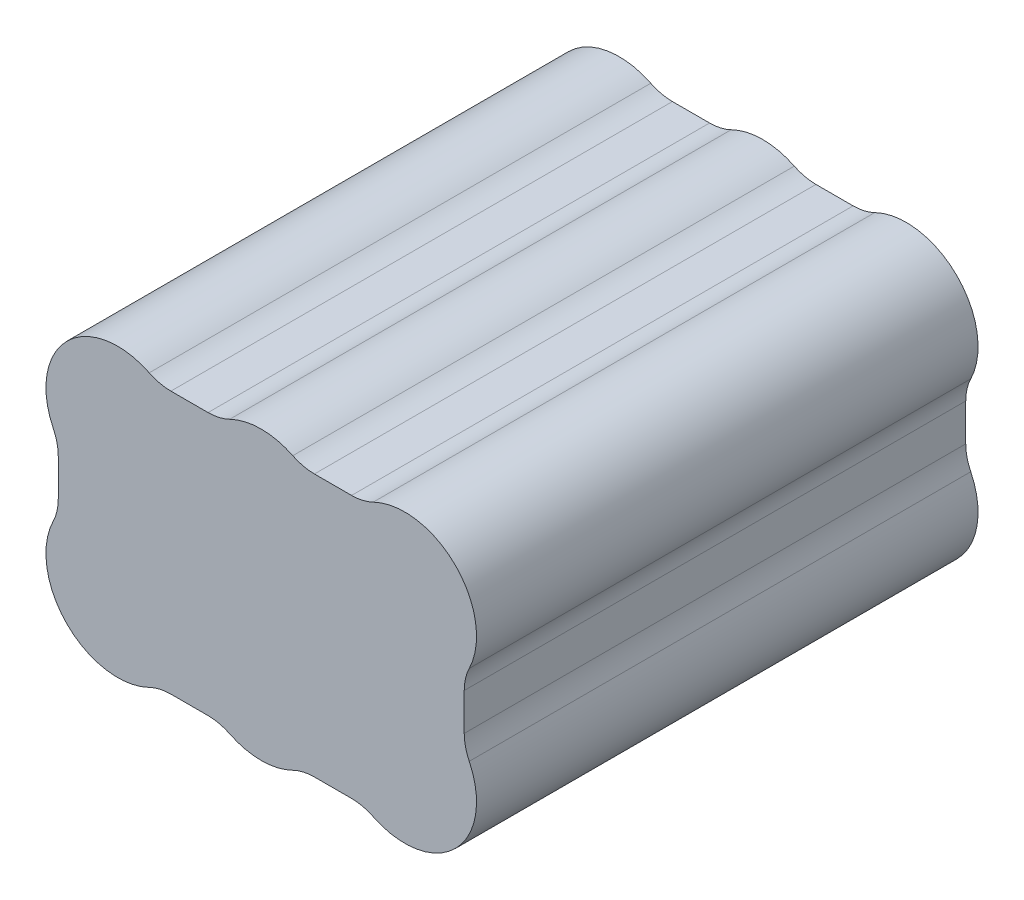
SolidWorks part; units mm, degrees
ref_plane "Front Plane" through (0, 0, 0) normal (0, 0, 1) x (1, 0, 0)
ref_plane "Top Plane" through (0, 0, 0) normal (0, 1, 0) x (1, 0, 0)
ref_plane "Right Plane" through (0, 0, 0) normal (1, 0, 0) x (0, 0, -1)
sketch "Sketch1" plane through (0, 0, 0) normal (0, 0, 1) x (1, 0, 0)
  line L0 (3150.6162, 2845.8822) -> (3155.4064, 2845.8822)
  line L1 (3169.1201, 2845.8822) -> (3173.9103, 2845.8822)
  line L2 (3150.6162, 2879.715) -> (3155.4064, 2879.715)
  line L3 (3169.1201, 2879.715) -> (3173.9103, 2879.715)
  line L4 (3136.0949, 2860.4035) -> (3136.0949, 2865.1937)
  line L5 (3188.4316, 2860.4035) -> (3188.4316, 2865.1937)
  arc A0 (3176.701, 2845.2361) -> (3189.0777, 2857.6127) centre (3180.7671, 2853.5467) ccw
  arc A1 (3158.1971, 2845.2361) -> (3166.3293, 2845.2361) centre (3162.2632, 2853.5467) ccw
  arc A2 (3135.4488, 2857.6127) -> (3147.8254, 2845.2361) centre (3143.7593, 2853.5467) ccw
  arc A3 (3150.6162, 2845.8822) -> (3147.8254, 2845.2361) centre (3150.6162, 2839.5322) ccw
  arc A4 (3158.1971, 2845.2361) -> (3155.4064, 2845.8822) centre (3155.4064, 2839.5322) ccw
  arc A5 (3169.1201, 2845.8822) -> (3166.3293, 2845.2361) centre (3169.1201, 2839.5322) ccw
  arc A6 (3176.701, 2845.2361) -> (3173.9103, 2845.8822) centre (3173.9103, 2839.5322) ccw
  arc A7 (3189.0777, 2867.9845) -> (3176.701, 2880.3611) centre (3180.7671, 2872.0506) ccw
  arc A8 (3166.3293, 2880.3611) -> (3158.1971, 2880.3611) centre (3162.2632, 2872.0506) ccw
  arc A9 (3147.8254, 2880.3611) -> (3135.4488, 2867.9845) centre (3143.7593, 2872.0506) ccw
  arc A10 (3147.8254, 2880.3611) -> (3150.6162, 2879.715) centre (3150.6162, 2886.065) ccw
  arc A11 (3155.4064, 2879.715) -> (3158.1971, 2880.3611) centre (3155.4064, 2886.065) ccw
  arc A12 (3166.3293, 2880.3611) -> (3169.1201, 2879.715) centre (3169.1201, 2886.065) ccw
  arc A13 (3173.9103, 2879.715) -> (3176.701, 2880.3611) centre (3173.9103, 2886.065) ccw
  arc A14 (3135.4488, 2857.6127) -> (3136.0949, 2860.4035) centre (3129.7449, 2860.4035) ccw
  arc A15 (3136.0949, 2865.1937) -> (3135.4488, 2867.9845) centre (3129.7449, 2865.1937) ccw
  arc A16 (3188.4316, 2860.4035) -> (3189.0777, 2857.6127) centre (3194.7816, 2860.4035) ccw
  arc A17 (3189.0777, 2867.9845) -> (3188.4316, 2865.1937) centre (3194.7816, 2865.1937) ccw
extrude "Boss-Extrude1" add sketch "Sketch1" along normal blind 64.6557
